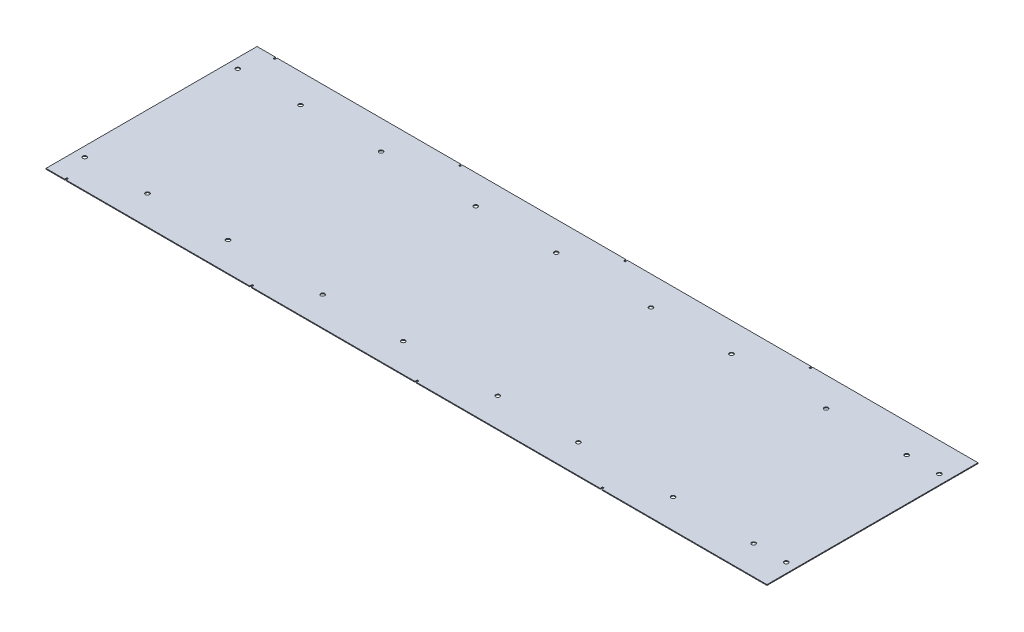
SolidWorks part; units mm, degrees
ref_plane "Front Plane" through (0, 0, 0) normal (0, 0, 1) x (1, 0, 0)
ref_plane "Top Plane" through (0, 0, 0) normal (0, 1, 0) x (1, 0, 0)
ref_plane "Right Plane" through (0, 0, 0) normal (1, 0, 0) x (0, 0, -1)
sketch "Sketch1" plane through (0, 0, 0) normal (0, 1, 0) x (1, 0, 0)
  line L0 (0, 0) -> (25, 0) construction
  line L9 (25, 0) -> (255, 0) construction
  line L10 (255, 0) -> (460, 0) construction
  line L12 (460, 0) -> (690, 0) construction
  line L14 (690, 0) -> (895, 0) construction
  line L16 (895, 0) -> (895, 262) construction
  line L65 (895, 262) -> (690, 262) construction
  line L66 (690, 262) -> (460, 262) construction
  line L67 (460, 262) -> (255, 262) construction
  line L68 (255, 262) -> (25, 262) construction
  line L69 (25, 262) -> (0, 262) construction
  line L70 (0, 262) -> (0, 0) construction
  line L71 (25, 226) -> (255, 226) construction
  line L72 (25, 262) -> (25, 0) construction
  line L73 (255, 226) -> (460, 226) construction
  line L74 (255, 262) -> (255, 0) construction
  line L75 (460, 226) -> (690, 226) construction
  line L76 (460, 262) -> (460, 0) construction
  line L77 (690, 226) -> (895, 226) construction
  line L78 (690, 262) -> (690, 0) construction
  line L79 (0, 0) -> (23, 0)
  line L80 (23, 0) -> (23, 3)
  line L81 (23, 3) -> (25, 3)
  line L82 (25, 3) -> (25, 0)
  line L83 (25, 0) -> (253, 0)
  line L84 (253, 0) -> (253, 3)
  line L85 (253, 3) -> (255, 3)
  line L86 (255, 3) -> (255, 0)
  line L87 (255, 0) -> (458, 0)
  line L88 (458, 0) -> (458, 3)
  line L89 (458, 3) -> (460, 3)
  line L90 (460, 3) -> (460, 0)
  line L91 (460, 0) -> (688, 0)
  line L92 (688, 0) -> (688, 3)
  line L93 (688, 3) -> (690, 3)
  line L94 (690, 3) -> (690, 0)
  line L95 (690, 0) -> (895, 0)
  line L96 (895, 0) -> (895, 262)
  line L97 (895, 262) -> (690, 262)
  line L98 (690, 262) -> (690, 259)
  line L99 (690, 259) -> (688, 259)
  line L100 (688, 259) -> (688, 262)
  line L101 (688, 262) -> (460, 262)
  line L102 (460, 262) -> (460, 259)
  line L103 (460, 259) -> (458, 259)
  line L104 (458, 259) -> (458, 262)
  line L105 (458, 262) -> (255, 262)
  line L106 (255, 262) -> (255, 259)
  line L107 (255, 259) -> (253, 259)
  line L108 (253, 259) -> (253, 262)
  line L109 (253, 262) -> (25, 262)
  line L110 (25, 262) -> (25, 259)
  line L111 (25, 259) -> (23, 259)
  line L112 (23, 259) -> (23, 262)
  line L113 (23, 262) -> (0, 262)
  line L114 (0, 262) -> (0, 0)
  line L115 (25, 3) -> (688, 3) construction
  line L116 (25, 259) -> (688, 259) construction
  line L117 (0, 131) -> (140, 131) construction
  line L118 (25, 36) -> (255, 36) construction
  line L119 (255, 36) -> (460, 36) construction
  line L120 (460, 36) -> (690, 36) construction
  line L121 (690, 36) -> (895, 36) construction
  line L122 (90, 36) -> (190, 36) construction
  line L123 (90, 36) -> (90, 226) construction
  line L124 (90, 226) -> (190, 226) construction
  line L125 (190, 36) -> (190, 226) construction
  line L126 (90, 36) -> (190, 226) construction
  line L127 (90, 226) -> (190, 36) construction
  line L128 (407.5, 36) -> (307.5, 36) construction
  line L129 (407.5, 36) -> (407.5, 226) construction
  line L130 (407.5, 226) -> (307.5, 226) construction
  line L131 (307.5, 36) -> (307.5, 226) construction
  line L132 (407.5, 36) -> (307.5, 226) construction
  line L133 (407.5, 226) -> (307.5, 36) construction
  line L134 (625, 36) -> (525, 36) construction
  line L135 (625, 36) -> (625, 226) construction
  line L136 (625, 226) -> (525, 226) construction
  line L137 (525, 36) -> (525, 226) construction
  line L138 (625, 36) -> (525, 226) construction
  line L139 (625, 226) -> (525, 36) construction
  line L140 (742.5, 226) -> (842.5, 226) construction
  line L141 (742.5, 226) -> (742.5, 36) construction
  line L142 (742.5, 36) -> (842.5, 36) construction
  line L143 (842.5, 226) -> (842.5, 36) construction
  line L144 (742.5, 226) -> (842.5, 36) construction
  line L145 (742.5, 36) -> (842.5, 226) construction
  line L146 (140, 131) -> (357.5, 131) construction
  line L147 (357.5, 131) -> (575, 131) construction
  line L148 (575, 131) -> (792.5, 131) construction
  line L149 (792.5, 131) -> (792.5, 226) construction
  line L150 (25, 226) -> (12, 226) construction
  line L151 (575, 131) -> (575, 226) construction
  line L152 (12, 226) -> (12, 36) construction
  line L153 (357.5, 131) -> (357.5, 226) construction
  line L154 (12, 36) -> (25, 36) construction
  line L155 (140, 131) -> (140, 226) construction
  line L156 (883, 226) -> (883, 36) construction
  circle A0 centre (90, 226) radius 2.5
  circle A1 centre (190, 226) radius 2.5
  circle A2 centre (307.5, 226) radius 2.5
  circle A3 centre (407.5, 226) radius 2.5
  circle A4 centre (525, 226) radius 2.5
  circle A5 centre (625, 226) radius 2.5
  circle A6 centre (742.5, 226) radius 2.5
  circle A7 centre (842.5, 226) radius 2.5
  circle A8 centre (842.5, 36) radius 2.5
  circle A9 centre (742.5, 36) radius 2.5
  circle A10 centre (625, 36) radius 2.5
  circle A11 centre (525, 36) radius 2.5
  circle A12 centre (407.5, 36) radius 2.5
  circle A13 centre (307.5, 36) radius 2.5
  circle A14 centre (190, 36) radius 2.5
  circle A15 centre (90, 36) radius 2.5
  circle A16 centre (12, 36) radius 2.5
  circle A17 centre (12, 226) radius 2.5
  circle A18 centre (883, 226) radius 2.5
  circle A19 centre (883, 36) radius 2.5
  point P79 (357.5, 131)
  point P80 (140, 131)
  point P89 (575, 131)
  point P94 (792.5, 131)
  dimension "D9" = 100
  dimension "D14" = 5
  dimension "D15" = 5
  dimension "D16" = 5
  dimension "D18" = 12
  dimension "D19" = 5
  dimension "D20" = 5
  dimension "D1" = 25
  dimension "D2" = 230
  dimension "D3" = 205
  dimension "D4" = 230
  dimension "D5" = 205
  dimension "D6" = 262
  dimension "D7" = 3
  dimension "D8" = 2
  dimension "D10" = 100
  dimension "D11" = 100
  dimension "D12" = 100
  dimension "D13" = 190
  dimension "D17" = 12
extrude "Boss-Extrude1" add sketch "Sketch1" along normal blind 1
